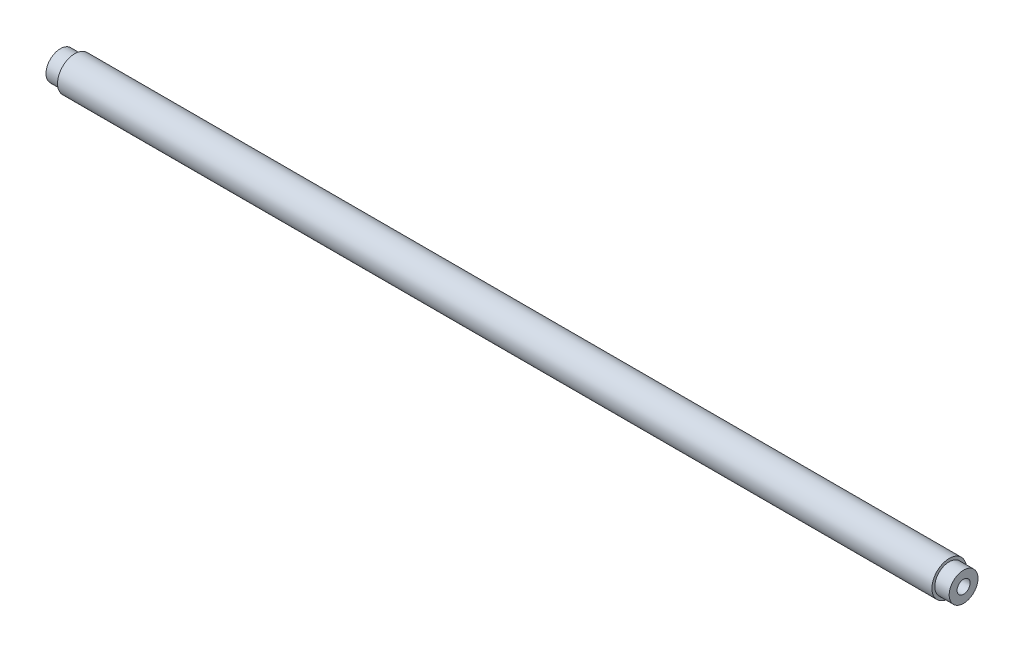
SolidWorks part; units mm, degrees
ref_plane "Ön Düzlem" through (0, 0, 0) normal (0, 0, 1) x (1, 0, 0)
ref_plane "Üst Düzlem" through (0, 0, 0) normal (0, 1, 0) x (1, 0, 0)
ref_plane "Sağ Düzlem" through (0, 0, 0) normal (1, 0, 0) x (0, 0, -1)
sketch "Çizim1" plane through (0, 0, 0) normal (0, 0, 1) x (1, 0, 0)
  line L0 (-235, 0) -> (235, 0)
  line L1 (-235, 0) -> (-235, 7.5)
  line L2 (-235, 7.5) -> (-227.5, 7.5)
  line L3 (-227.5, 7.5) -> (-227.5, 9)
  line L4 (-227.5, 9) -> (227.5, 9)
  line L5 (227.5, 9) -> (227.5, 7.5)
  line L6 (227.5, 7.5) -> (235, 7.5)
  line L7 (235, 7.5) -> (235, 0)
  point P2 (0, 0)
  dimension "D1" = 470
  dimension "D2" = 7.5
  dimension "D3" = 9
  dimension "D4" = 455
revolve "Döndür2" add sketch "Çizim1" angle 360 about L0
hole_wizard "M8 Dişli Delik3" positions "Çizim3" profile "Çizim4" tap size "M8" standard "ISO"
sketch "Çizim3" plane through (-235, 0, 0) normal (-1, 0, 0) x (0, 0, 1)
  point P0 (0, 0)
sketch "Çizim4" plane through (-235, 0, 0) normal (0, 1, 0) x (0, 0, 1)
  line L0 (0, 0) -> (0, 24.2929)
  line L1 (0, 24.2929) -> (3.4, 22.25)
  line L2 (3.4, 22.25) -> (3.4, 0)
  line L5 (3.4, 0) -> (0, 0)
  line L10 (0, 24.2929) -> (-3.4, 22.25) construction
  line L11 (0, -6.35) -> (0, 107.95) construction
  dimension "Tap Drill Dia." = 6.8
  dimension "Tap Drill Depth" = 22.25
  dimension "Drill Angle" = 118
cosmetic thread "Delik Dişi1" parameters "D1"=16, "D2"=8
mirror "Aynalama1" about plane through (0, 0, 0) normal (1, 0, 0) of "M8 Dişli Delik3"
cosmetic thread "Delik Dişi2" parameters "D1"=16, "D2"=8
